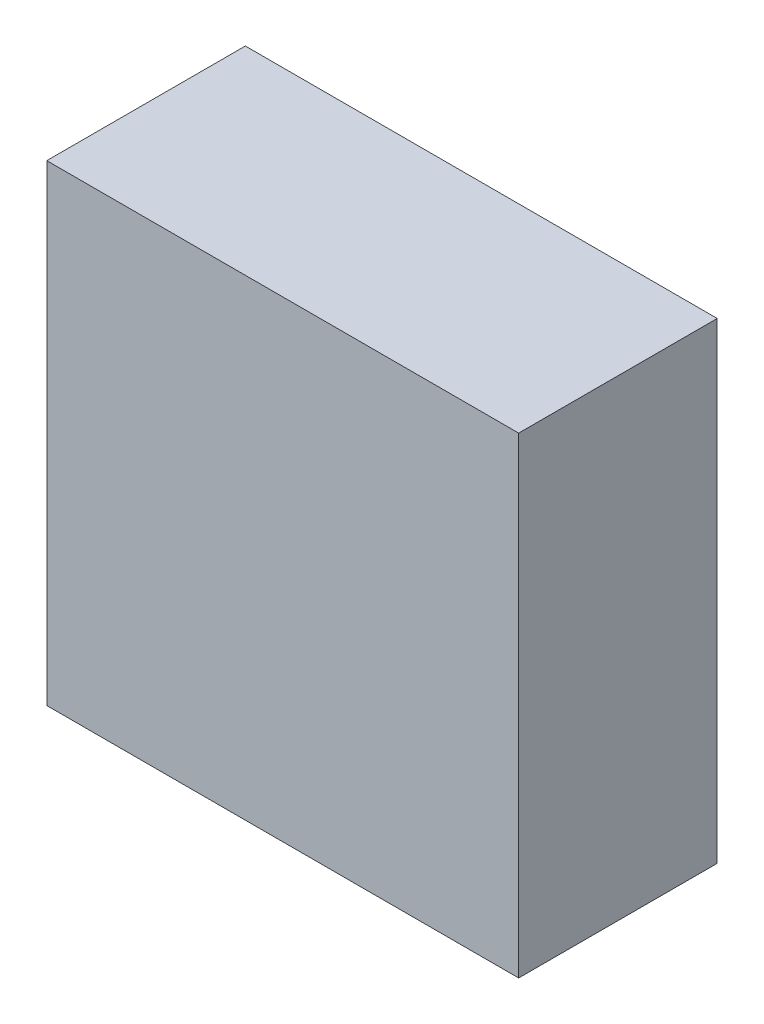
SolidWorks part; units mm, degrees
ref_plane "Front Plane" through (0, 0, 0) normal (0, 0, 1) x (1, 0, 0)
ref_plane "Top Plane" through (0, 0, 0) normal (0, 1, 0) x (1, 0, 0)
ref_plane "Right Plane" through (0, 0, 0) normal (1, 0, 0) x (0, 0, -1)
sketch "Sketch1" plane through (0, 0, 0) normal (0, 0, 1) x (1, 0, 0)
  line L1 (10.1, 10.1) -> (-10.1, 10.1)
  line L2 (10.1, 10.1) -> (10.1, -10.1)
  line L3 (10.1, -10.1) -> (-10.1, -10.1)
  line L4 (-10.1, 10.1) -> (-10.1, -10.1)
  line L5 (10.1, 10.1) -> (-10.1, -10.1) construction
  line L6 (10.1, -10.1) -> (-10.1, 10.1) construction
  point P0 (0, 0)
  dimension "D1" = 20.2
  dimension "D2" = 20.2
extrude "Boss-Extrude1" add sketch "Sketch1" along normal blind 8.5
